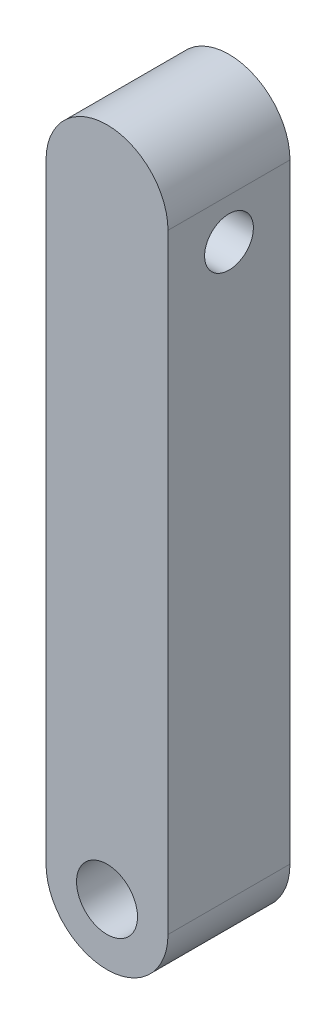
SolidWorks part; units mm, degrees
ref_plane "Front Plane" through (0, 0, 0) normal (0, 0, 1) x (1, 0, 0)
ref_plane "Top Plane" through (0, 0, 0) normal (0, 1, 0) x (1, 0, 0)
ref_plane "Right Plane" through (0, 0, 0) normal (1, 0, 0) x (0, 0, -1)
sketch "Sketch2" plane through (0, 0, 0) normal (0, 0, 1) x (1, 0, 0)
  line L0 (0, -50) -> (0, 50) construction
  line L1 (-10, -50) -> (-10, 50)
  line L2 (10, -50) -> (10, 50)
  arc A0 (-10, -50) -> (10, -50) centre (0, -50) ccw
  arc A1 (10, 50) -> (-10, 50) centre (0, 50) ccw
  circle A3 centre (0, -50) radius 5
  point P2 (0, 0)
  dimension "D1" = 100
  dimension "D2" = 20
extrude "Boss-Extrude1" add sketch "Sketch2" along normal blind 20
sketch "Sketch4" plane through (10, 0, 0) normal (1, 0, 0) x (0, 0, -1)
  circle A0 centre (-10, 43.3554) radius 4
extrude "Cut-Extrude1" cut sketch "Sketch4" against normal blind 26
ref_plane "Plane2" through (0, 0, 25) normal (0, 0, 1) x (1, 0, 0)
sketch "Sketch6" plane through (0, 0, 25) normal (0, 0, 1) x (1, 0, 0)
  line L1 (0, -50) -> (0, -78.2411) construction
  line L4 (0, -50) -> (0, -60) construction
  line L5 (-11.1495, -60) -> (0, -60) construction
  line L6 (0, -60) -> (10.9197, -60) construction
  arc A0 (-10, -50) -> (10, -50) centre (0, -50) ccw construction
  point P0 (-0.25, -60)
  point P4 (0, -60)
  dimension "D1" = 0.25
ref_plane "Plane3" through (0, 0, 0) normal (1, 0, 0) x (0, 0, -1)
sketch "Sketch7" plane through (0, 0, 0) normal (1, 0, 0) x (0, 0, -1)
  line L0 (-20, -50) -> (0, -50) construction
  point P2 (-10, -50)
